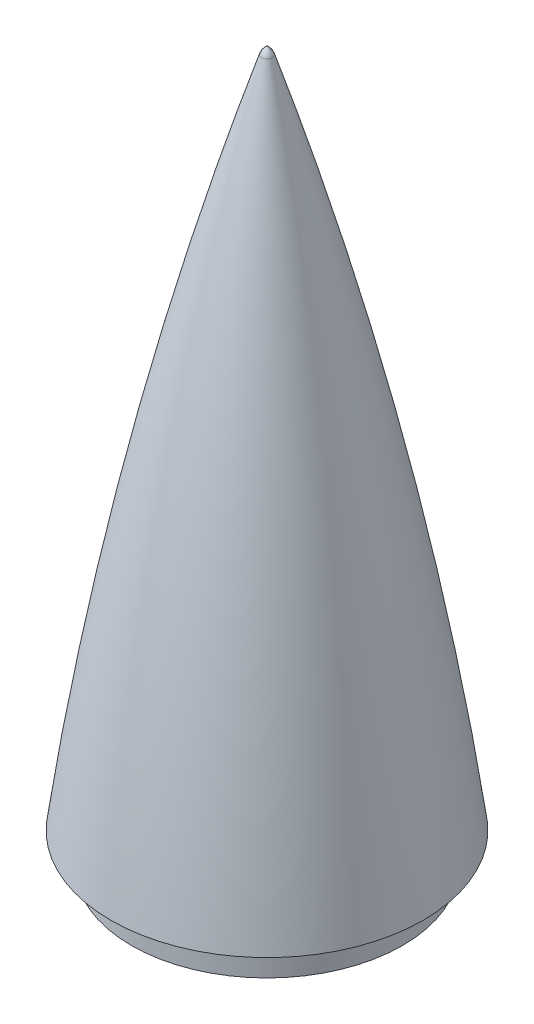
SolidWorks part; units mm, degrees
ref_plane "Front Plane" through (0, 0, 0) normal (0, 0, 1) x (1, 0, 0)
ref_plane "Top Plane" through (0, 0, 0) normal (0, 1, 0) x (1, 0, 0)
ref_plane "Right Plane" through (0, 0, 0) normal (1, 0, 0) x (0, 0, -1)
sketch "Sketch1" plane through (0, 0, 0) normal (1, 0, 0) x (0, 0, -1)
  line L0 (0, 0) -> (0, 323.85) construction
  line L1 (-51.054, 0) -> (-26.0858, 0) construction
  line L2 (-51.054, 0) -> (-51.054, -118.0029) construction
  line L4 (-26.0858, 0) -> (-26.0858, -64.897) construction
  line L5 (-48.5109, 2.54) -> (-23.5458, 2.54) construction
  line L6 (-23.5458, 2.54) -> (-23.5458, -64.897) construction
  line L7 (-26.0858, -64.897) -> (-23.5458, -64.897) construction
  line L8 (0, 323.85) -> (0, 315.496) construction
  line L9 (-41.743, 139.7) -> (-36.663, 139.7) construction
  line L10 (-36.663, 139.7) -> (-36.663, 131.6014) construction
  line L11 (-36.663, 131.6014) -> (-41.1972, 123.7478) construction
  line L12 (-39.1119, 140.208) -> (-41.6748, 140.208)
  line L13 (0, 315.496) -> (0, 321.31)
  line L14 (-39.1119, 140.208) -> (-36.155, 140.208)
  line L15 (-36.155, 140.208) -> (-36.155, 131.6014)
  line L16 (-36.155, 131.6014) -> (-33.615, 131.6014)
  line L17 (-33.615, 131.6014) -> (-33.615, 142.748)
  line L18 (-33.615, 142.748) -> (-38.385, 145.502)
  line L19 (0, 321.31) -> (0, 323.85) construction
  arc A2 (-51.054, 0) -> (-41.743, 139.7) centre (1001.6092, 0) cw construction
  arc A3 (-48.5109, 2.54) -> (-41.1972, 123.7478) centre (1001.6092, 0) cw construction
  arc A4 (-48.5109, 2.54) -> (2.4168, 323.0686) centre (1001.6092, 0) cw construction
  arc A5 (-41.743, 139.7) -> (0, 323.85) centre (1001.6092, 0) cw construction
  arc A6 (-51.054, 0) -> (0, 323.85) centre (1001.6092, 0) cw construction
  arc A7 (-41.1972, 123.7478) -> (-39.1119, 140.208) centre (1001.6092, 0) cw construction
  arc A8 (0, 323.85) -> (-1.4456, 319.3445) centre (1001.6092, 0) ccw construction
  arc A9 (0, 315.496) -> (-38.385, 145.502) centre (1001.6092, 0) ccw
  arc A10 (-38.385, 145.502) -> (0, 315.496) centre (1001.6092, 0) cw construction
  arc A11 (-1.4456, 319.3445) -> (0, 321.31) centre (2.1849, 318.1887) cw
  arc A12 (-1.4456, 319.3445) -> (-41.6748, 140.208) centre (1001.6092, 0) ccw
  dimension "D6" = 139.7
  dimension "D12" = 2.54
  dimension "D16" = 3.81
  dimension "D1" = 323.85
  dimension "D2" = 64.897
  dimension "D3" = 51.054
  dimension "D4" = 26.0858
  dimension "D5" = 2.54
  dimension "D7" = 5.08
  dimension "D8" = 8.0986
  dimension "D9" = 150
  dimension "D10" = 0.508
  dimension "D11" = 120
  dimension "D13" = 0.508
  dimension "D14" = 2.54
  dimension "D15" = 2.54
revolve "Revolve1" add sketch "Sketch1" angle 360 about L0
fillet "Fillet1" radius 0.762 1 edges at (0, 140.208, -36.155)
